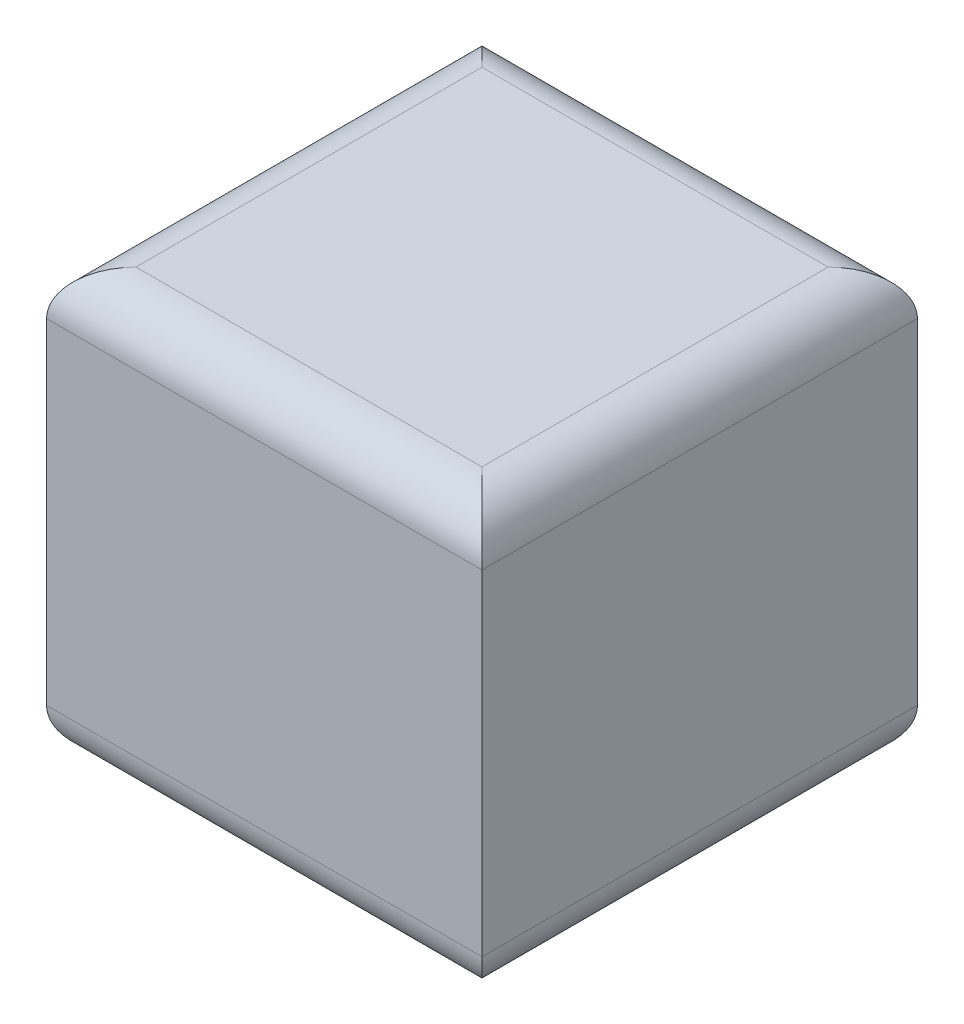
SolidWorks part; units mm, degrees
ref_plane "Front Plane" through (0, 0, 0) normal (0, 0, 1) x (1, 0, 0)
ref_plane "Top Plane" through (0, 0, 0) normal (0, 1, 0) x (1, 0, 0)
ref_plane "Right Plane" through (0, 0, 0) normal (1, 0, 0) x (0, 0, -1)
sketch "Sketch1" plane through (0, 0, 0) normal (0, 1, 0) x (1, 0, 0)
  line L1 (-4.875, -4.875) -> (4.875, -4.875)
  line L2 (-4.875, -4.875) -> (-4.875, 4.875)
  line L3 (-4.875, 4.875) -> (4.875, 4.875)
  line L4 (4.875, -4.875) -> (4.875, 4.875)
  line L5 (-4.875, -4.875) -> (4.875, 4.875) construction
  line L6 (-4.875, 4.875) -> (4.875, -4.875) construction
  point P0 (0, 0)
  dimension "D1" = 9.75
extrude "Boss-Extrude1" add sketch "Sketch1" along normal mid plane 9.5
fillet "Fillet1" radius 1 8 edges at (0, -4.75, -4.875) (-4.875, -4.75, 0) (0, -4.75, 4.875) (4.875, -4.75, 0) (0, 4.75, 4.875) (-4.875, 4.75, 0) (0, 4.75, -4.875) (4.875, 4.75, 0)
